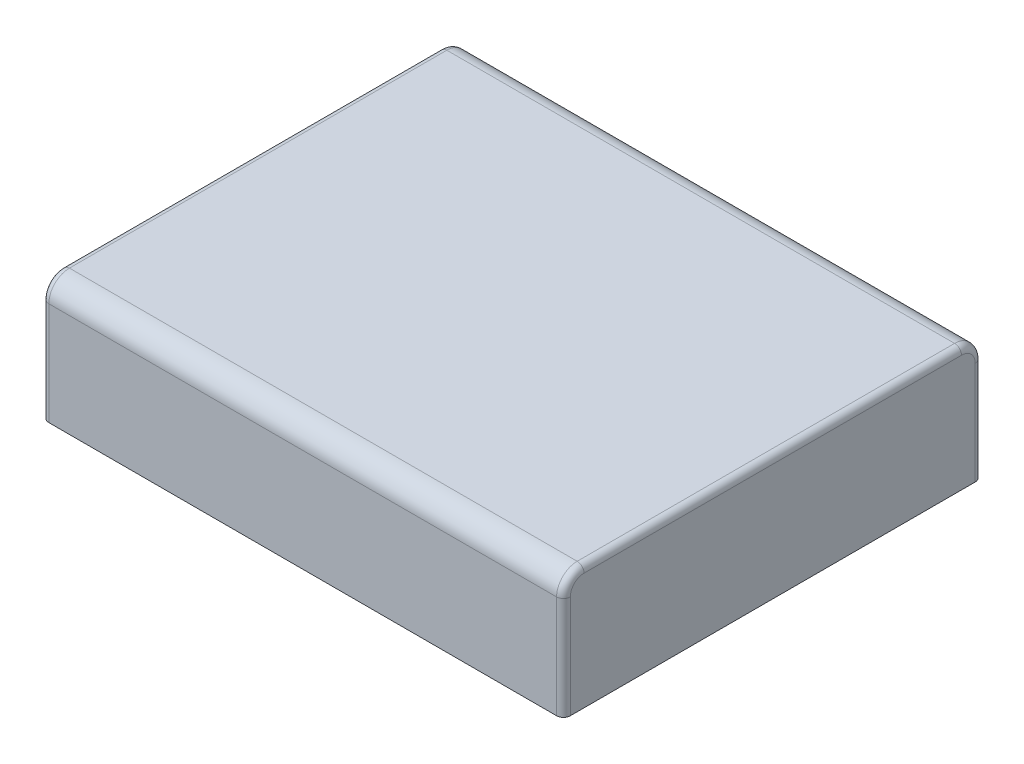
SolidWorks part; units mm, degrees
ref_plane "前基準面" through (0, 0, 0) normal (0, 0, 1) x (1, 0, 0)
ref_plane "上基準面" through (0, 0, 0) normal (0, 1, 0) x (1, 0, 0)
ref_plane "右基準面" through (0, 0, 0) normal (1, 0, 0) x (0, 0, -1)
sketch "草圖1" plane through (0, 0, 0) normal (0, 1, 0) x (1, 0, 0)
  line L1 (-38, 30.5) -> (38, 30.5)
  line L2 (-38, 30.5) -> (-38, -30.5)
  line L3 (-38, -30.5) -> (38, -30.5)
  line L4 (38, 30.5) -> (38, -30.5)
  line L5 (-38, 30.5) -> (38, -30.5) construction
  line L6 (-38, -30.5) -> (38, 30.5) construction
  point P0 (0, 0)
  dimension "D1" = 76
  dimension "D2" = 61
extrude "填料-伸長1" add sketch "草圖1" along normal blind 18
fillet "圓角1" radius 3 2 edges at (0, 18, 30.5) (0, 18, -30.5)
fillet "圓角2" radius 1 10 edges at (38, 17.1213, -29.6213) (38, 18, 0) (38, 17.1213, 29.6213) (-38, 17.1213, -29.6213) (-38, 18, 0) (-38, 17.1213, 29.6213) (-38, 7.5, -30.5) (38, 7.5, -30.5) (38, 7.5, 30.5) (-38, 7.5, 30.5)
